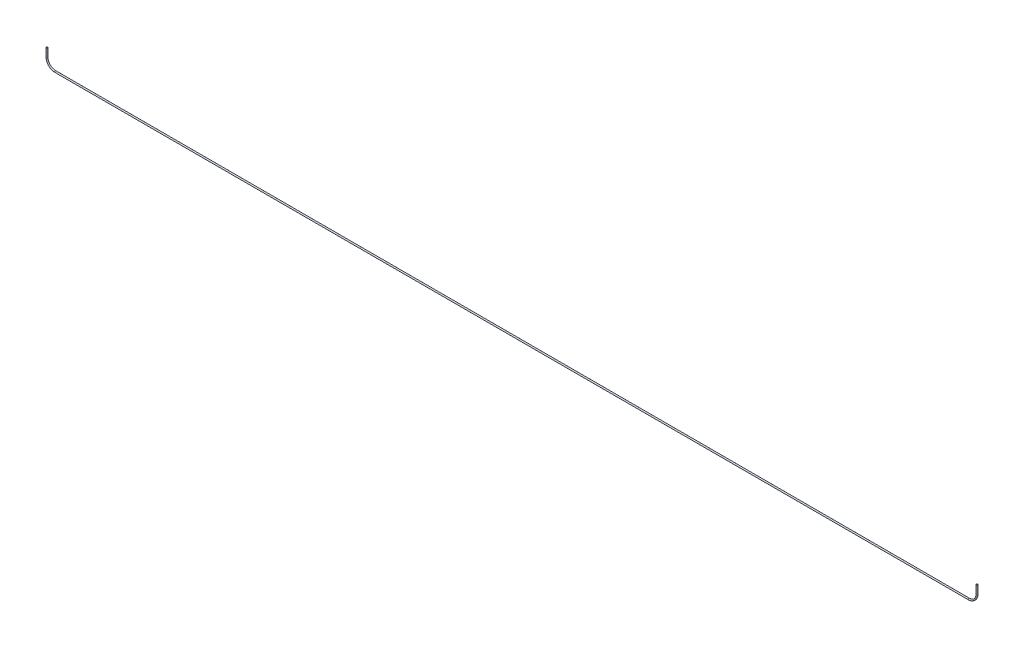
SolidWorks part; units mm, degrees
ref_plane "Front Plane" through (0, 0, 0) normal (0, 0, 1) x (1, 0, 0)
ref_plane "Top Plane" through (0, 0, 0) normal (0, 1, 0) x (1, 0, 0)
ref_plane "Right Plane" through (0, 0, 0) normal (1, 0, 0) x (0, 0, -1)
sketch "Sketch1" plane through (0, 0, 0) normal (0, 0, 1) x (1, 0, 0)
  line L0 (4125, 0) -> (-4125, 0)
  line L1 (-4200, 75) -> (-4200, 150)
  line L2 (0, 443.7864) -> (0, -507.096) construction
  line L3 (4200, 75) -> (4200, 150)
  arc A0 (-4125, 0) -> (-4200, 75) centre (-4125, 75) cw
  arc A1 (4125, 0) -> (4200, 75) centre (4125, 75) ccw
  point P6 (-4200, 0)
  point P13 (0, 0)
  dimension "D3" = 75
  dimension "D1" = 4200
  dimension "D2" = 150
sweep "Sweep1" add path "Sketch1" circular profile diameter 12.7 parameters "D3"=12.7
